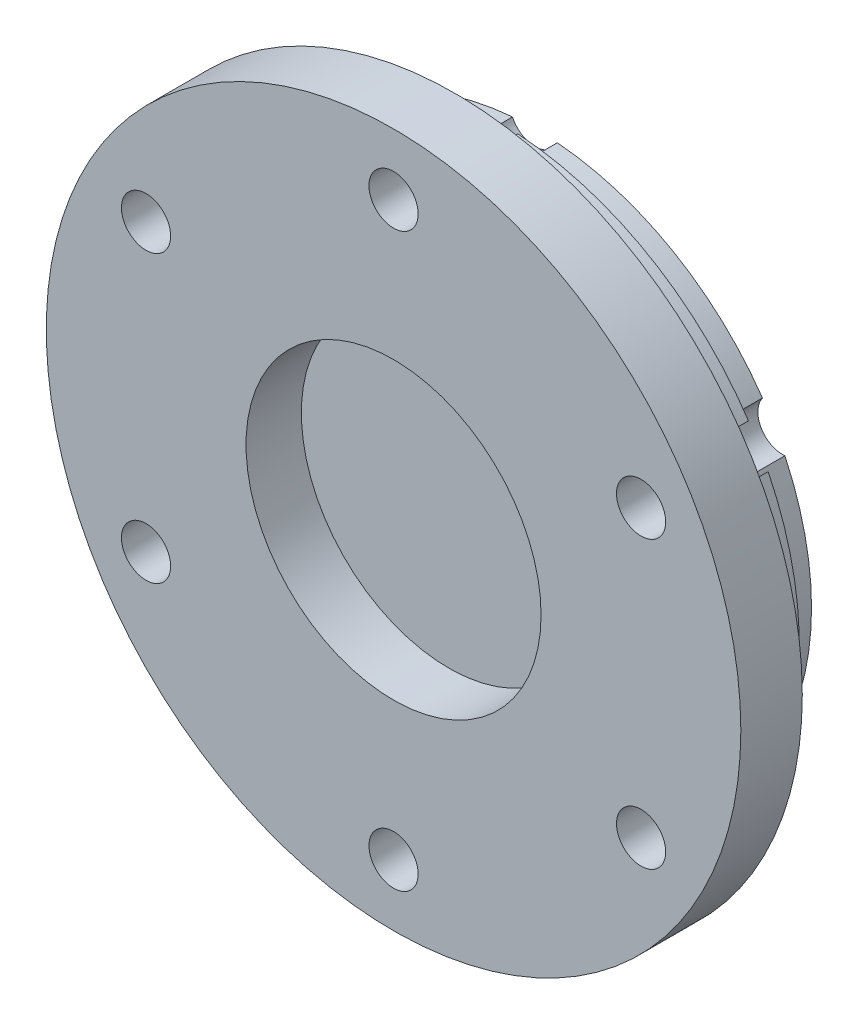
SolidWorks part; units mm, degrees
ref_plane "Front Plane" through (0, 0, 0) normal (0, 0, 1) x (1, 0, 0)
ref_plane "Top Plane" through (0, 0, 0) normal (0, 1, 0) x (1, 0, 0)
ref_plane "Right Plane" through (0, 0, 0) normal (1, 0, 0) x (0, 0, -1)
sketch "Sketch1" plane through (0, 0, 0) normal (1, 0, 0) x (0, 0, -1)
  line L0 (0, 0) -> (79.2027, 0) construction
  line L1 (0, 0) -> (0, 28.25)
  line L2 (0, 28.25) -> (5, 28.25)
  line L3 (5, 28.25) -> (5, 24.5)
  line L4 (5, 24.5) -> (8.5, 24.5)
  line L5 (8.5, 24.5) -> (8.5, 22.5)
  line L6 (8.5, 22.5) -> (26.5, 22.5)
  line L7 (26.5, 22.5) -> (26.5, 0)
  line L8 (26.5, 0) -> (0, 0)
  dimension "D1" = 28.25
  dimension "D2" = 5
  dimension "D3" = 3.5
  dimension "18" = 18
  dimension "D4" = 22.5
  dimension "D5" = 2
revolve "Revolve1" add sketch "Sketch1" angle 360 about L0
sketch "Sketch2" plane through (0, 0, -5) normal (0, 0, -1) x (-1, 0, 0)
  line L0 (0, 0) -> (0, 28.25) construction
  circle A0 centre (0, 0) radius 28.25 construction
  circle A1 centre (0, 23.25) radius 2
  dimension "D1" = 4
  dimension "D2" = 23.25
extrude "Cut-Extrude1" cut sketch "Sketch2" against normal through all both and the other way through all
pattern_circular "CirPattern1" count 6 over 360 about axis through (0, 0, 0) along (0, 0, 1) of "Cut-Extrude1"
sketch "Sketch5" plane through (0, 0, -26.5) normal (0, 0, -1) x (-1, 0, 0)
  circle A0 centre (0, 0) radius 17.5 construction
  arc A1 (-1.8224, 22.4261) -> (-18.5104, 12.7913) centre (0, 0) ccw
  circle A3 centre (0, 17.5) radius 2
  arc A16 (-1.8224, 22.4261) -> (-18.5104, 12.7913) centre (0, 0) ccw
  arc A17 (-20.3328, 9.6348) -> (-18.5104, 12.7913) centre (-20.1351, 11.625) ccw
  arc A18 (-20.3328, 9.6348) -> (-18.5104, 12.7913) centre (-20.1351, 11.625) ccw
  arc A19 (-20.3328, 9.6348) -> (-20.3328, -9.6348) centre (0, 0) ccw
  arc A20 (-20.3328, 9.6348) -> (-20.3328, -9.6348) centre (0, 0) ccw
  arc A21 (-18.5104, -12.7913) -> (-20.3328, -9.6348) centre (-20.1351, -11.625) ccw
  arc A22 (-18.5104, -12.7913) -> (-20.3328, -9.6348) centre (-20.1351, -11.625) ccw
  arc A23 (-18.5104, -12.7913) -> (-1.8224, -22.4261) centre (0, 0) ccw
  arc A24 (-18.5104, -12.7913) -> (-1.8224, -22.4261) centre (0, 0) ccw
  arc A25 (1.8224, -22.4261) -> (-1.8224, -22.4261) centre (0, -23.25) ccw
  arc A26 (1.8224, -22.4261) -> (-1.8224, -22.4261) centre (0, -23.25) ccw
  arc A27 (1.8224, -22.4261) -> (18.5104, -12.7913) centre (0, 0) ccw
  arc A28 (1.8224, -22.4261) -> (18.5104, -12.7913) centre (0, 0) ccw
  arc A29 (20.3328, -9.6348) -> (18.5104, -12.7913) centre (20.1351, -11.625) ccw
  arc A30 (20.3328, -9.6348) -> (18.5104, -12.7913) centre (20.1351, -11.625) ccw
  arc A31 (20.3328, -9.6348) -> (20.3328, 9.6348) centre (0, 0) ccw
  arc A32 (20.3328, -9.6348) -> (20.3328, 9.6348) centre (0, 0) ccw
  arc A33 (18.5104, 12.7913) -> (20.3328, 9.6348) centre (20.1351, 11.625) ccw
  arc A34 (18.5104, 12.7913) -> (20.3328, 9.6348) centre (20.1351, 11.625) ccw
  arc A35 (18.5104, 12.7913) -> (1.8224, 22.4261) centre (0, 0) ccw
  arc A36 (18.5104, 12.7913) -> (1.8224, 22.4261) centre (0, 0) ccw
  arc A37 (-1.8224, 22.4261) -> (1.8224, 22.4261) centre (0, 23.25) ccw
  arc A38 (-1.8224, 22.4261) -> (1.8224, 22.4261) centre (0, 23.25) ccw
  dimension "D3" = 4
extrude "Cut-Extrude2" cut sketch "Sketch5" against normal blind 10 flip side to cut
pattern_circular "CirPattern2" count 6 over 360 about axis through (0, 0, 0) along (0, 0, 1) of "Cut-Extrude2"
sketch "Sketch6" plane through (0, 0, 0) normal (0, 0, 1) x (1, 0, 0)
  circle A0 centre (0, 0) radius 12
  dimension "D1" = 24
extrude "Cut-Extrude3" cut sketch "Sketch6" against normal blind 4.5
sketch "Sketch7" plane through (0, 0, -26.5) normal (0, 0, -1) x (-1, 0, 0)
  arc A12 (-1.8224, 22.4261) -> (-18.5104, 12.7913) centre (0, 0) ccw
  arc A13 (-20.3328, 9.6348) -> (-18.5104, 12.7913) centre (-20.1351, 11.625) ccw
  arc A14 (-20.3328, 9.6348) -> (-20.3328, -9.6348) centre (0, 0) ccw
  arc A15 (-18.5104, -12.7913) -> (-20.3328, -9.6348) centre (-20.1351, -11.625) ccw
  arc A16 (-18.5104, -12.7913) -> (-1.8224, -22.4261) centre (0, 0) ccw
  arc A17 (1.8224, -22.4261) -> (-1.8224, -22.4261) centre (0, -23.25) ccw
  arc A18 (1.8224, -22.4261) -> (18.5104, -12.7913) centre (0, 0) ccw
  arc A19 (20.3328, -9.6348) -> (18.5104, -12.7913) centre (20.1351, -11.625) ccw
  arc A20 (20.3328, -9.6348) -> (20.3328, 9.6348) centre (0, 0) ccw
  arc A21 (18.5104, 12.7913) -> (20.3328, 9.6348) centre (20.1351, 11.625) ccw
  arc A22 (18.5104, 12.7913) -> (1.8224, 22.4261) centre (0, 0) ccw
  arc A23 (-1.8224, 22.4261) -> (1.8224, 22.4261) centre (0, 23.25) ccw
  arc A24 (-1.8224, 22.4261) -> (-18.5104, 12.7913) centre (0, 0) ccw
  arc A25 (-20.3328, 9.6348) -> (-18.5104, 12.7913) centre (-20.1351, 11.625) ccw
  arc A26 (-20.3328, 9.6348) -> (-20.3328, -9.6348) centre (0, 0) ccw
  arc A27 (-18.5104, -12.7913) -> (-20.3328, -9.6348) centre (-20.1351, -11.625) ccw
  arc A28 (-18.5104, -12.7913) -> (-1.8224, -22.4261) centre (0, 0) ccw
  arc A29 (1.8224, -22.4261) -> (-1.8224, -22.4261) centre (0, -23.25) ccw
  arc A30 (1.8224, -22.4261) -> (18.5104, -12.7913) centre (0, 0) ccw
  arc A31 (20.3328, -9.6348) -> (18.5104, -12.7913) centre (20.1351, -11.625) ccw
  arc A32 (20.3328, -9.6348) -> (20.3328, 9.6348) centre (0, 0) ccw
  arc A33 (18.5104, 12.7913) -> (20.3328, 9.6348) centre (20.1351, 11.625) ccw
  arc A34 (18.5104, 12.7913) -> (1.8224, 22.4261) centre (0, 0) ccw
  arc A35 (-1.8224, 22.4261) -> (1.8224, 22.4261) centre (0, 23.25) ccw
  dimension "D1" = 0
extrude "Cut-Extrude4" cut sketch "Sketch7" against normal blind 15
equation "\"Module\"= 1.5mm"
equation "\"Number of teeth\"= 15"
equation "\"Internal Bearing 'r'\"= 2.5mm"
equation "\"External Bearing 'r'\" = 11.75mm"
equation "\"Bearing Depth\"= 4mm"
equation "\"Planet Path Radius\"= 10.5mm + ( ( \"Number of teeth\" + 2 ) * \"Module\" ) / 2"
equation "\"Pin Radius\"= 4mm"
equation "\"Fastening Holes\"= 4mm"
equation "\"D1@Sketch1\"=\"Planet Path Radius\" + 5"
equation "\"D1@Sketch2\"=\"Fastening Holes\""
equation "\"D2@Sketch2\"=\"Planet Path Radius\""
equation "\"Number of Planets\"= 3"
equation "\"D1@CirPattern1\"=\"Number of Planets\"*2"
equation "\"D3@Sketch5\"=\"Fastening Holes\""
equation "\"D1@Sketch6\"=\"External Bearing 'r'\"*2+0.5'''''''''"
equation "\"D1@Cut-Extrude3\"=\"Bearing Depth\"+.5"
equation "\"Big Bearing E.R.\"= 29mm"
equation "\"Big Bearing I.R.\"= 22.5mm"
equation "\"D4@Sketch1\"=\"Big Bearing I.R.\""
